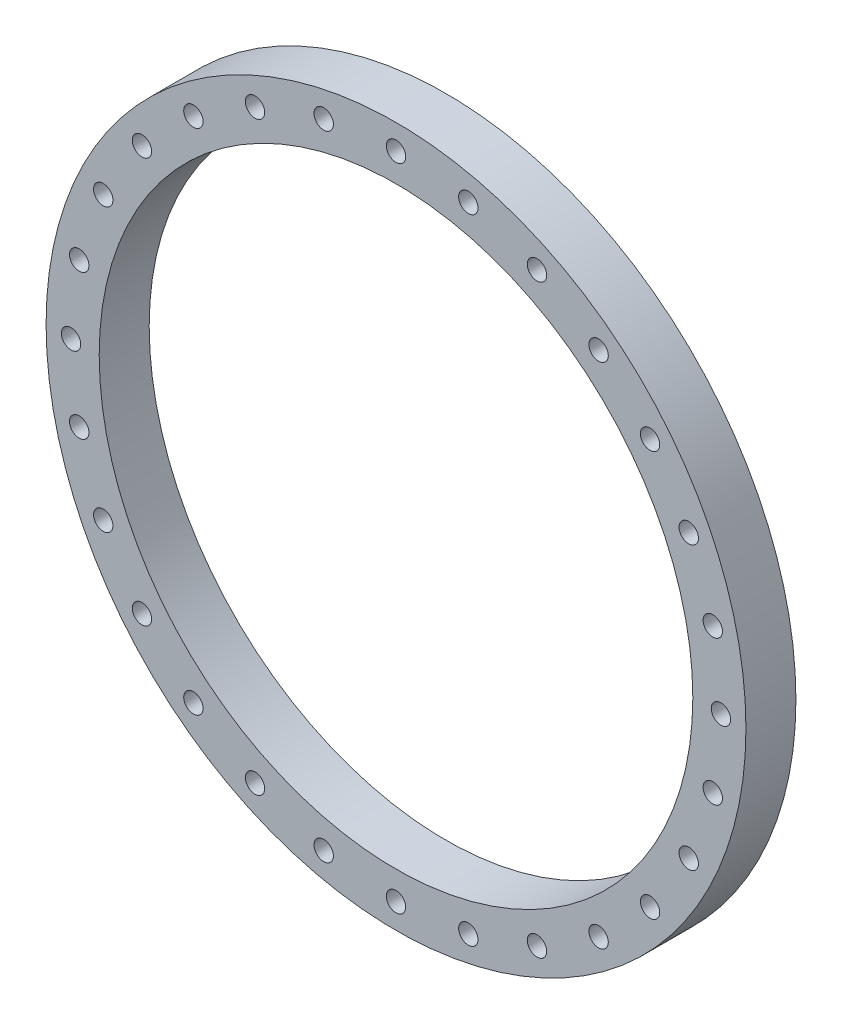
SolidWorks part; units mm, degrees
ref_plane "前视基准面" through (0, 0, 0) normal (0, 0, 1) x (1, 0, 0)
ref_plane "上视基准面" through (0, 0, 0) normal (0, 1, 0) x (1, 0, 0)
ref_plane "右视基准面" through (0, 0, 0) normal (1, 0, 0) x (0, 0, -1)
sketch "草图1" plane through (0, 0, 0) normal (0, 0, 1) x (1, 0, 0)
  circle A0 centre (0, 0) radius 47.5
  circle A1 centre (0, 0) radius 56
  circle A2 centre (0, 0) radius 52 construction
  circle A3 centre (0, 52) radius 1.55
  circle A4 centre (11.5711, 50.6963) radius 1.55
  circle A5 centre (22.562, 46.8504) radius 1.55
  circle A6 centre (32.4215, 40.6552) radius 1.55
  circle A7 centre (40.6552, 32.4215) radius 1.55
  circle A8 centre (46.8504, 22.562) radius 1.55
  circle A9 centre (50.6963, 11.5711) radius 1.55
  circle A10 centre (52, 0) radius 1.55
  circle A11 centre (50.6963, -11.5711) radius 1.55
  circle A12 centre (46.8504, -22.562) radius 1.55
  circle A13 centre (40.6552, -32.4215) radius 1.55
  circle A14 centre (32.4215, -40.6552) radius 1.55
  circle A15 centre (22.562, -46.8504) radius 1.55
  circle A16 centre (11.5711, -50.6963) radius 1.55
  circle A17 centre (0, -52) radius 1.55
  circle A18 centre (-11.5711, -50.6963) radius 1.55
  circle A19 centre (-22.562, -46.8504) radius 1.55
  circle A20 centre (-32.4215, -40.6552) radius 1.55
  circle A21 centre (-40.6552, -32.4215) radius 1.55
  circle A22 centre (-46.8504, -22.562) radius 1.55
  circle A23 centre (-50.6963, -11.5711) radius 1.55
  circle A24 centre (-52, 0) radius 1.55
  circle A25 centre (-50.6963, 11.5711) radius 1.55
  circle A26 centre (-46.8504, 22.562) radius 1.55
  circle A27 centre (-40.6552, 32.4215) radius 1.55
  circle A28 centre (-32.4215, 40.6552) radius 1.55
  circle A29 centre (-22.562, 46.8504) radius 1.55
  circle A30 centre (-11.5711, 50.6963) radius 1.55
  point P8 (-21.4859, 40.2524)
  point P9 (0, 0)
  point P63 (0, 0)
  dimension "D1" = 95
  dimension "D2" = 112
  dimension "D3" = 104
  dimension "D4" = 3.1
  dimension "D5" = 28
extrude "凸台-拉伸1" add sketch "草图1" along normal blind 8
